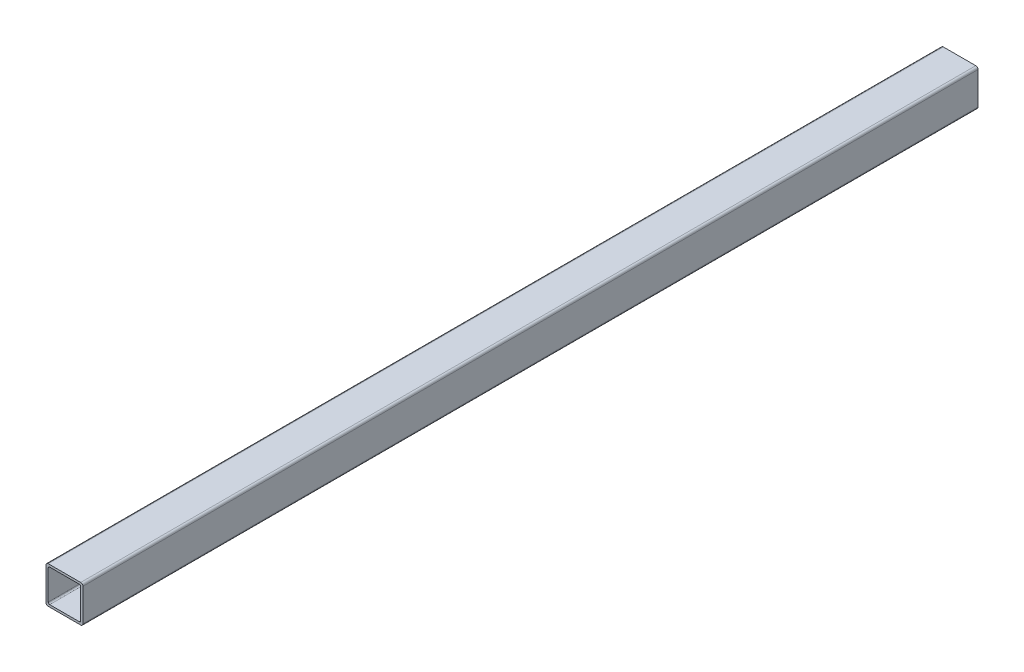
SolidWorks part; units mm, degrees
material "AISI 1020"
ref_plane "Спереди" through (0, 0, 0) normal (0, 0, 1) x (1, 0, 0)
ref_plane "Сверху" through (0, 0, 0) normal (0, 1, 0) x (1, 0, 0)
ref_plane "Справа" through (0, 0, 0) normal (1, 0, 0) x (0, 0, -1)
sketch "Эскиз1" plane through (0, 0, 0) normal (0, 0, 1) x (1, 0, 0)
  line L0 (4484.0362, 100) -> (100, 100) construction
  line L1 (0, 5060) -> (0, 0) construction
  line B0 (6, 100) -> (94, 100)
  line B1 (0, 94) -> (0, 6)
  line B2 (6, 0) -> (94, 0)
  line B3 (100, 94) -> (100, 6)
  line B4 (10, 94) -> (90, 94)
  line B5 (6, 90) -> (6, 10)
  line B6 (10, 6) -> (90, 6)
  line B7 (94, 90) -> (94, 10)
  arc B8 (0, 6) -> (6, 0) centre (6, 6) ccw
  arc B9 (94, 0) -> (100, 6) centre (94, 6) ccw
  arc B10 (94, 100) -> (100, 94) centre (94, 94) cw
  arc B11 (6, 100) -> (0, 94) centre (6, 94) ccw
  arc B12 (6, 10) -> (10, 6) centre (10, 10) ccw
  arc B13 (90, 6) -> (94, 10) centre (90, 10) ccw
  arc B14 (90, 94) -> (94, 90) centre (90, 90) cw
  arc B15 (10, 94) -> (6, 90) centre (10, 90) ccw
sketch_block_instance "Пр_тр_100х100х6-1"
sketch_block "Пр_тр_100х100х6" parameters "D3"=6, "D4"=4, "D1"=100, "D2"=6
extrude "Бобышка-Вытянуть1" add sketch "Эскиз1" along normal up to surface (2425 mm away)
